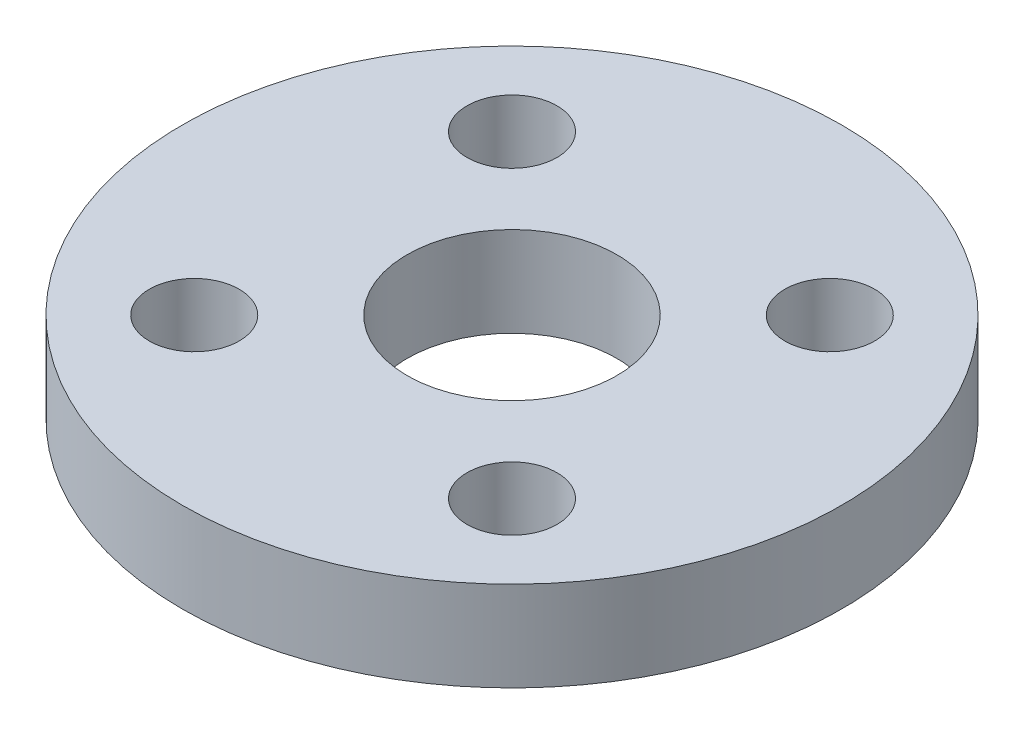
SolidWorks part; units mm, degrees
ref_plane "Front Plane" through (0, 0, 0) normal (0, 0, 1) x (1, 0, 0)
ref_plane "Top Plane" through (0, 0, 0) normal (0, 1, 0) x (1, 0, 0)
ref_plane "Right Plane" through (0, 0, 0) normal (1, 0, 0) x (0, 0, -1)
sketch "Sketch1" plane through (0, 0, 0) normal (0, 1, 0) x (1, 0, 0)
  line L0 (0, 0) -> (0, -7.5) construction
  line L1 (-5.3033, -5.3033) -> (0, 0) construction
  circle A0 centre (0, 0) radius 11
  circle A1 centre (0, 0) radius 7.5 construction
  circle A2 centre (-5.3033, -5.3033) radius 1.5
  circle A3 centre (-5.3033, 5.3033) radius 1.5
  circle A4 centre (5.3033, 5.3033) radius 1.5
  circle A5 centre (5.3033, -5.3033) radius 1.5
  point P16 (0, 0)
  dimension "D1" = 22
  dimension "D2" = 15
  dimension "D3" = 3
  dimension "D4" = 45
  dimension "D5" = 4
extrude "Boss-Extrude1" add sketch "Sketch1" along normal blind 3
sketch "Sketch2" plane through (0, 3, 0) normal (0, 1, 0) x (1, 0, 0)
  circle A0 centre (0, 0) radius 3.5
  dimension "D1" = 7
extrude "Cut-Extrude1" cut sketch "Sketch2" against normal blind 10
